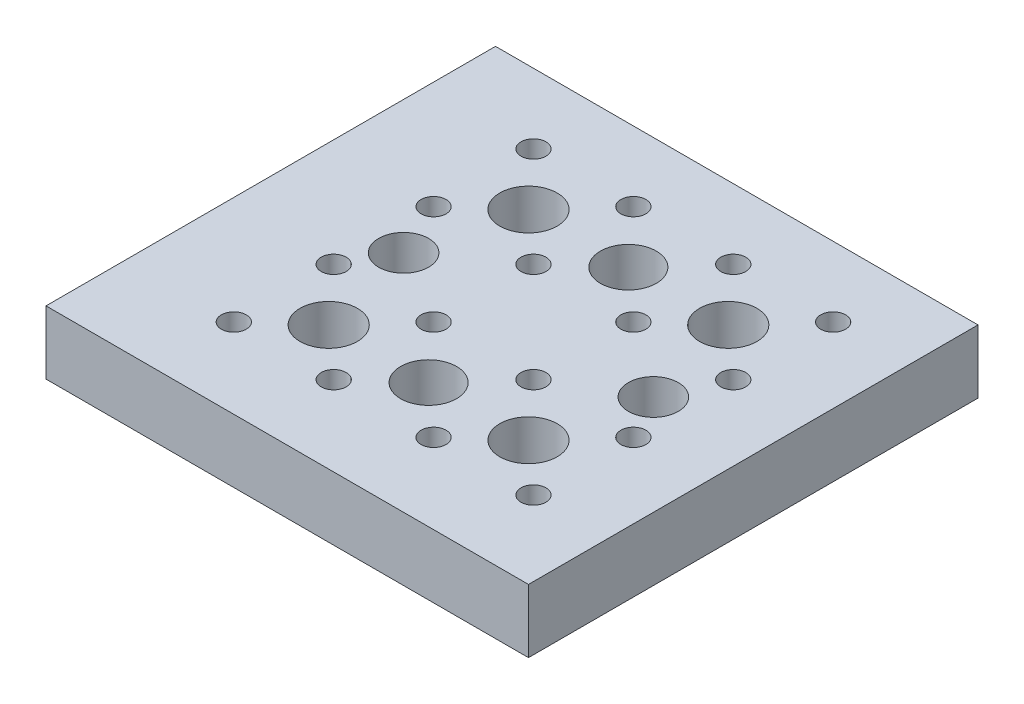
SolidWorks part; units mm, degrees
ref_plane "Front Plane" through (0, 0, 0) normal (0, 0, 1) x (1, 0, 0)
ref_plane "Top Plane" through (0, 0, 0) normal (0, 1, 0) x (1, 0, 0)
ref_plane "Right Plane" through (0, 0, 0) normal (1, 0, 0) x (0, 0, -1)
sketch "Sketch1" plane through (0, 0, 0) normal (0, 1, 0) x (1, 0, 0)
  line L1 (0, 0) -> (48.3, 0)
  line L2 (0, 0) -> (0, -45)
  line L3 (0, -45) -> (48.3, -45)
  line L4 (48.3, 0) -> (48.3, -45)
  circle A0 centre (15.8, -12.5) radius 2.875
  circle A1 centre (35.8, -12.5) radius 2.875
  circle A2 centre (15.8, -32.5) radius 2.875
  circle A3 centre (35.8, -32.5) radius 2.875
  circle A4 centre (10.8, -7) radius 1.25
  circle A5 centre (20.8, -7) radius 1.25
  circle A6 centre (30.8, -7) radius 1.25
  circle A7 centre (40.8, -7) radius 1.25
  circle A8 centre (20.8, -17) radius 1.25
  circle A9 centre (30.8, -17) radius 1.25
  circle A10 centre (40.8, -17) radius 1.25
  circle A11 centre (20.8, -27) radius 1.25
  circle A12 centre (30.8, -27) radius 1.25
  circle A13 centre (40.8, -27) radius 1.25
  circle A14 centre (20.8, -37) radius 1.25
  circle A15 centre (30.8, -37) radius 1.25
  circle A16 centre (40.8, -37) radius 1.25
  circle A17 centre (10.8, -17) radius 1.25
  circle A18 centre (10.8, -27) radius 1.25
  circle A19 centre (10.8, -37) radius 1.25
  circle A20 centre (25.8, -12.5) radius 2.8
  circle A21 centre (25.8, -32.5) radius 2.8
  circle A22 centre (13.3, -22.5) radius 2.5
  circle A23 centre (38.3, -22.5) radius 2.5
  point P51 (0, 0)
  point P54 (0, 0)
  point P55 (0, -22.5)
  dimension "D3" = 5.75
  dimension "D8" = 2.5
  dimension "D16" = 5.6
  dimension "D19" = 5
  dimension "D1" = 48.3
  dimension "D2" = 45
  dimension "D4" = 15.8
  dimension "D5" = 20
  dimension "D6" = 20
  dimension "D7" = 12.5
  dimension "D9" = 10.8
  dimension "D10" = 7
  dimension "D13" = 10
  dimension "D14" = 10
  dimension "D15" = 10
  dimension "D17" = 25
  dimension "D18" = 12.5
  dimension "D11" = 4
  dimension "D12" = 4
extrude "Boss-Extrude1" add sketch "Sketch1" along normal blind 6.35
equation "\"D14@Sketch1\"=\"D13@Sketch1\""
equation "\"D18@Sketch1\"=\"D17@Sketch1\"/2"
